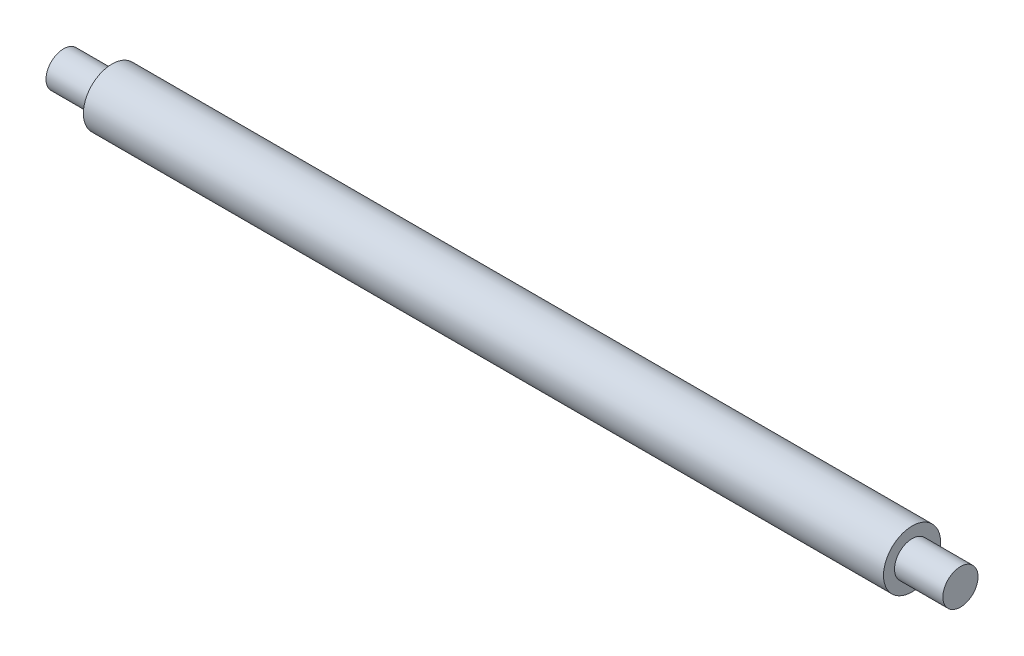
SolidWorks part; units mm, degrees
ref_plane "Płaszczyzna przednia" through (0, 0, 0) normal (0, 0, 1) x (1, 0, 0)
ref_plane "Płaszczyzna górna" through (0, 0, 0) normal (0, 1, 0) x (1, 0, 0)
ref_plane "Płaszczyzna prawa" through (0, 0, 0) normal (1, 0, 0) x (0, 0, -1)
sketch "Sketch1" plane through (0, 0, 0) normal (0, 0, 1) x (1, 0, 0)
  line L0 (0, 0) -> (204, 0)
  line L1 (204, 0) -> (204, 4)
  line L2 (204, 4) -> (193, 4)
  line L3 (193, 4) -> (193, 6.5)
  line L4 (193, 6.5) -> (11, 6.5)
  line L5 (11, 6.5) -> (11, 4)
  line L6 (11, 4) -> (0, 4)
  line L7 (0, 4) -> (0, 0)
  dimension "D1" = 182
  dimension "D2" = 11
  dimension "D3" = 4
  dimension "D4" = 6.5
  dimension "D5" = 4
revolve "Revolve1" add sketch "Sketch1" angle 360 about L0
